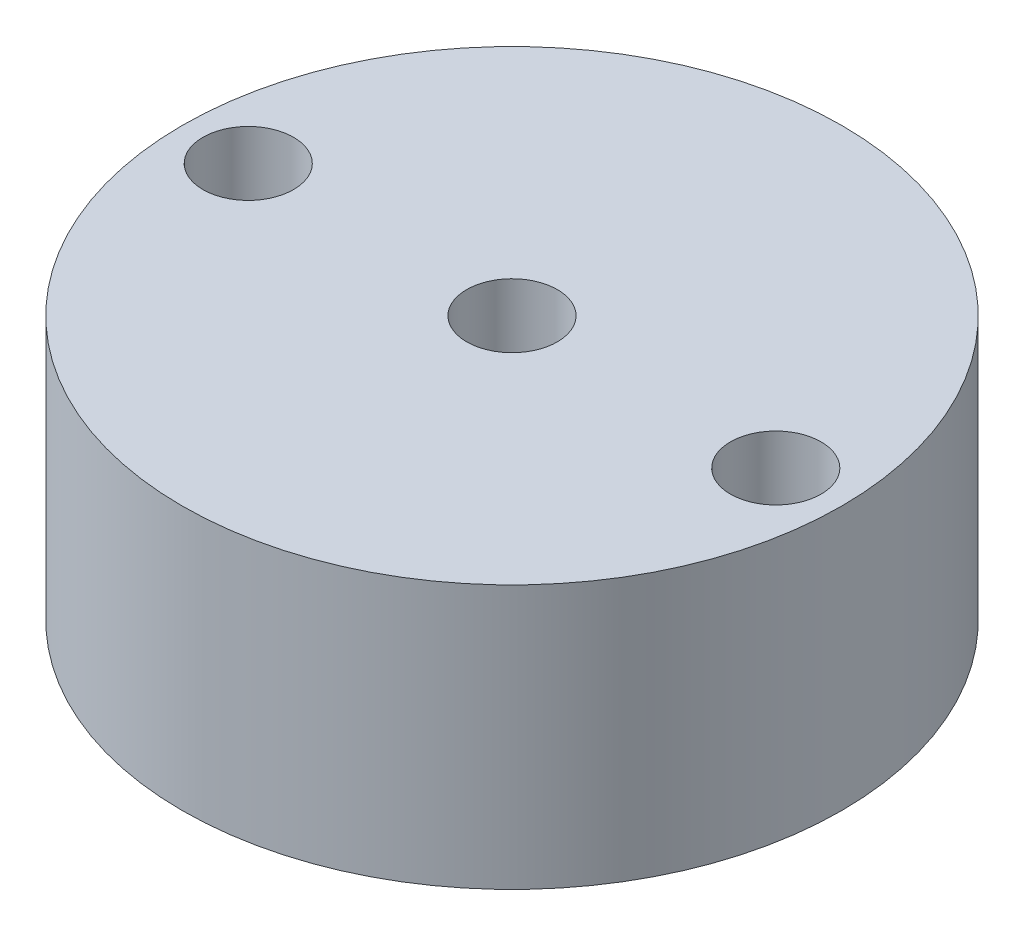
SolidWorks part; units mm, degrees
ref_plane "Front Plane" through (0, 0, 0) normal (0, 0, 1) x (1, 0, 0)
ref_plane "Top Plane" through (0, 0, 0) normal (0, 1, 0) x (1, 0, 0)
ref_plane "Right Plane" through (0, 0, 0) normal (1, 0, 0) x (0, 0, -1)
sketch "Sketch1" plane through (0, 0, 0) normal (0, 1, 0) x (1, 0, 0)
  circle A0 centre (0, 0) radius 2.1828
  circle A1 centre (12.7, 0) radius 2.1828
  circle A2 centre (-12.7, 0) radius 2.1828
  circle A3 centre (0, 0) radius 15.875
  point P12 (0, 0)
  dimension "D3" = 4.3656
  dimension "D4" = 4.3656
  dimension "D5" = 4.3656
  dimension "D6" = 31.75
  dimension "D1" = 12.7
  dimension "D2" = 12.7
extrude "Boss-Extrude1" add sketch "Sketch1" along normal blind 12.7
